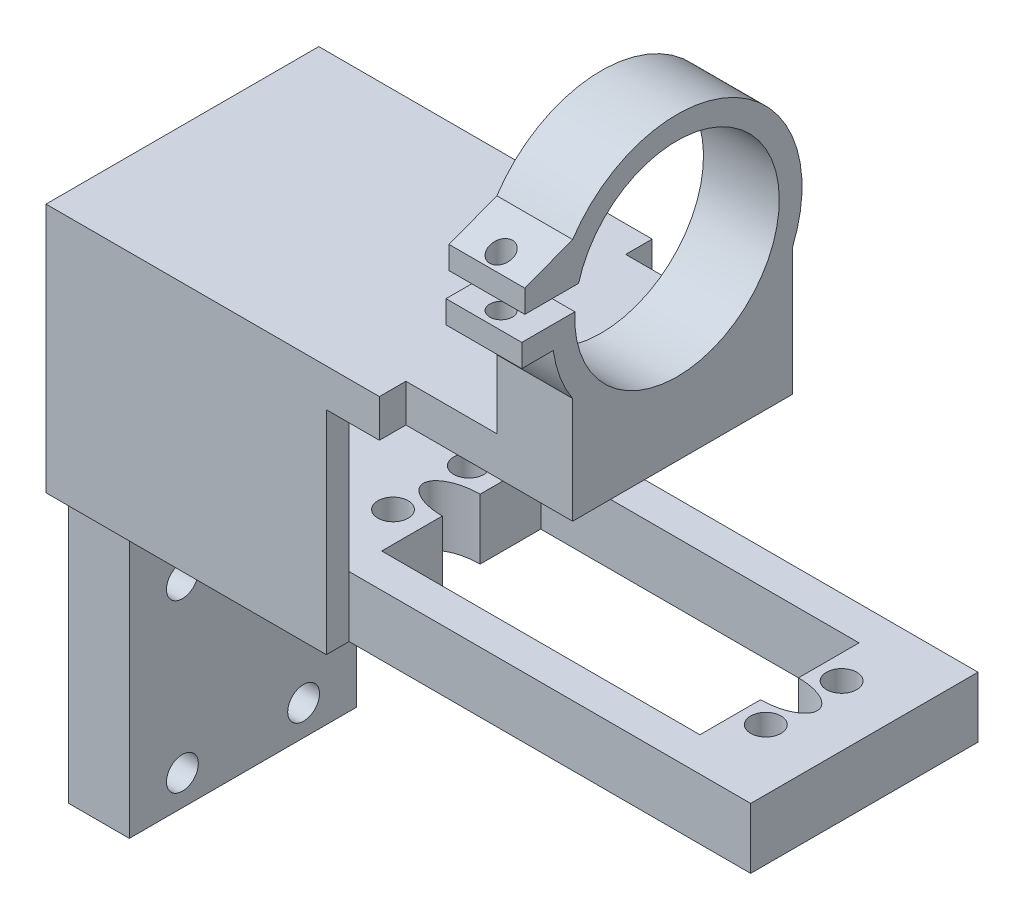
SolidWorks part; units mm, degrees
material "ABS"
ref_plane "前基準面" through (0, 0, 0) normal (0, 0, 1) x (1, 0, 0)
ref_plane "上基準面" through (0, 0, 0) normal (0, 1, 0) x (1, 0, 0)
ref_plane "右基準面" through (0, 0, 0) normal (1, 0, 0) x (0, 0, -1)
sketch "草圖1" plane through (0, 0, 0) normal (0, 1, 0) x (1, 0, 0)
  line L1 (0, 0) -> (82, 0)
  line L2 (0, 0) -> (0, 30)
  line L3 (0, 30) -> (82, 30)
  line L4 (82, 0) -> (82, 30)
  dimension "D1" = 82
  dimension "D2" = 30
extrude "填料-伸長1" add sketch "草圖1" along normal blind 8
sketch "草圖2" plane through (0, 8, 0) normal (0, 1, 0) x (1, 0, 0)
  line L1 (28.8, 25.5) -> (70.8, 25.5)
  line L3 (28.8, 4.5) -> (70.8, 4.5)
  line L6 (82, 30) -> (0, 30) construction
  line L7 (28.8, 25.5) -> (28.8, 17.5)
  line L8 (70.8, 25.5) -> (70.8, 17.5)
  line L9 (70.8, 12.5) -> (70.8, 4.5)
  line L10 (28.8, 12.5) -> (28.8, 4.5)
  line L11 (0, 30) -> (0, 0) construction
  line L12 (82, 0) -> (82, 30) construction
  circle A0 centre (74, 20) radius 2
  circle A1 centre (74, 10) radius 2
  circle A2 centre (24.8, 20) radius 2
  circle A3 centre (24.8, 10) radius 2
  ellipse E0 centre (70.8, 15) end of major axis (75.8, 15) minor radius 2.5 (70.8, 12.5) -> (70.8, 17.5) ccw
  ellipse E1 centre (28.8, 15) end of major axis (33.8, 15) minor radius 2.5 (28.8, 17.5) -> (28.8, 12.5) ccw
  dimension "D4" = 10
  dimension "D1" = 21
  dimension "D2" = 42
  dimension "D3" = 4.5
  dimension "D5" = 10
  dimension "D6" = 10
  dimension "D7" = 10
  dimension "D8" = 5
  dimension "D9" = 5
  dimension "D10" = 10
  dimension "D11" = 8
  dimension "D12" = 10
  dimension "D13" = 8
  dimension "24.8" = 24.8
  dimension "D15" = 8
  dimension "D16" = 28.8
extrude "除料-伸長1" cut sketch "草圖2" against normal blind 8
sketch "草圖4" plane through (0, 8, 0) normal (0, 1, 0) x (1, 0, 0)
  line L0 (0, 30) -> (0, 0)
  line L9 (0, 0) -> (-8, 0)
  line L10 (-8, 0) -> (-8, 30)
  line L11 (-8, 30) -> (0, 30)
  dimension "D1" = 8
extrude "填料-伸長2" add sketch "草圖4" against normal blind 45
sketch "草圖14" plane through (0, 0, 0) normal (0, 0, 1) x (1, 0, 0)
  line L0 (0, 0) -> (0, -2)
  line L1 (0, -37) -> (0, 0) construction
  line L2 (0, -2) -> (2, 0)
  line L3 (0, 0) -> (82, 0) construction
  line L4 (2, 0) -> (0, 0)
  dimension "D1" = 2
  dimension "D2" = 2
extrude "填料-伸長5" add sketch "草圖14" against normal blind 30
sketch "草圖15" plane through (0, 0, 0) normal (1, 0, 0) x (0, 0, -1)
  line L0 (0, -37) -> (30, -37) construction
  line L1 (0, -37) -> (0, -2) construction
  circle A0 centre (7, -33) radius 2.1
  circle A5 centre (7, -11) radius 2.1
  circle A13 centre (23, -11) radius 2.1
  circle A16 centre (23, -33) radius 2.1
  circle A19 centre (15, -11) radius 2.1 [skipped]
  circle A20 centre (15, -33) radius 2.1 [skipped]
  dimension "D1" = 4
  dimension "D2" = 22
  dimension "D3" = 4.2
  dimension "D4" = 4.2
  dimension "D6" = 7
  dimension "D7" = 3
extrude "除料-伸長2" cut sketch "草圖15" against normal blind 10
sketch "草圖17" plane through (0, 8, 0) normal (0, 1, 0) x (1, 0, 0)
  line L1 (-8, 0) -> (29, 0)
  line L2 (-8, 0) -> (-8, -3)
  line L3 (-8, -3) -> (29, -3)
  line L4 (29, 0) -> (29, -3)
  line L5 (-8, 30) -> (29, 30)
  line L6 (-8, 30) -> (-8, 33)
  line L7 (-8, 33) -> (29, 33)
  line L8 (29, 30) -> (29, 33)
  dimension "D1" = 37
  dimension "D2" = 37
  dimension "D3" = 3
  dimension "D4" = 3
extrude "填料-伸長6" add sketch "草圖17" along normal blind 20 separate body
sketch "草圖18" plane through (0, 28, 0) normal (0, 1, 0) x (1, 0, 0)
  line L0 (-8, 33) -> (58, 33)
  line L1 (58, 33) -> (58, -3)
  line L2 (58, -3) -> (-8, -3)
  line L3 (-8, -3) -> (-8, 33)
  dimension "D1" = 66
extrude "填料-伸長7" add sketch "草圖18" along normal blind 5
sketch "草圖19" plane through (0, 8, 0) normal (0, -1, 0) x (-1, 0, 0)
  line L1 (-29, -3) -> (8, -3)
  line L2 (-29, -3) -> (-29, 0)
  line L3 (-29, 0) -> (8, 0)
  line L4 (8, -3) -> (8, 0)
  line L5 (8, 33) -> (-29, 33)
  line L6 (8, 33) -> (8, 30)
  line L7 (8, 30) -> (-29, 30)
  line L8 (-29, 33) -> (-29, 30)
extrude "填料-伸長8" add sketch "草圖19" along normal up to vertex
sketch "草圖20" plane through (0, 33, 0) normal (0, 1, 0) x (1, 0, 0)
  line L0 (58, -3) -> (58, 33) construction
  line L1 (58, 33) -> (36, 33)
  line L2 (58, 33) -> (58, 29.5)
  line L3 (58, 29.5) -> (36, 29.5)
  line L4 (36, 33) -> (36, 29.5)
  line L5 (58, -3) -> (36, -3)
  line L6 (58, -3) -> (58, 0.5)
  line L7 (58, 0.5) -> (36, 0.5)
  line L8 (36, -3) -> (36, 0.5)
  dimension "D1" = 29
  dimension "D2" = 3.5
  dimension "D3" = 22
  dimension "D4" = 22
extrude "除料-伸長3" cut sketch "草圖20" against normal up to vertex (5 mm away)
sketch "草圖21" plane through (58, 0, 0) normal (1, 0, 0) x (0, 0, -1)
  circle A0 centre (14.2747, 51.1133) radius 13.5
  circle A1 centre (14.2747, 51.1133) radius 16.5
  dimension "D1" = 27
  dimension "D2" = 33
extrude "填料-伸長9" add sketch "草圖21" against normal blind 10 separate body
sketch "草圖22" plane through (58, 0, 0) normal (1, 0, 0) x (0, 0, -1)
  line L1 (2.7516, 51.7967) -> (-7.0135, 51.7967)
  line L2 (2.7516, 51.7967) -> (2.7516, 54.7967)
  line L3 (2.7516, 54.7967) -> (-7.0135, 54.7967)
  line L4 (-7.0135, 51.7967) -> (-7.0135, 54.7967)
  point P0 (14.2747, 51.1133)
  dimension "D1" = 3
extrude "除料-伸長4" cut sketch "草圖22" against normal blind 10
sketch "草圖23" plane through (58, 0, 0) normal (1, 0, 0) x (0, 0, -1)
  line L0 (-1.8089, 54.7967) -> (-5.8089, 54.7967)
  line L1 (-5.8089, 54.7967) -> (-5.8089, 57.7967)
  line L2 (-5.8089, 57.7967) -> (0.5, 60.1967)
  line L3 (-2.2111, 51.7967) -> (-6.2111, 51.7967)
  line L4 (-6.2111, 51.7967) -> (-6.2111, 48.7967)
  line L5 (-6.2111, 48.7967) -> (-2.0618, 48.7967)
  line L6 (0.5, 42.03) -> (0.5, 33)
  line L7 (0.5, 33) -> (29.5, 33) construction
  line L8 (0.5, 33) -> (29.5, 33)
  line L9 (29.5, 33) -> (29.5, 44.754)
  line L10 (-1.8089, 54.7967) -> (0.5, 60.1967)
  line L11 (-2.2111, 51.7967) -> (-2.0618, 48.7967)
  line L12 (0.5, 42.03) -> (13.6406, 34.6255)
  line L13 (13.6406, 34.6255) -> (27.6208, 41.4111)
  line L14 (27.6208, 41.4111) -> (29.5, 44.754)
  arc A0 (-2.2111, 51.7967) -> (-1.8089, 54.7967) centre (14.2747, 51.1133) ccw construction
  dimension "D1" = 29
  dimension "D2" = 3
  dimension "D3" = 4
  dimension "D4" = 4
  dimension "D5" = 3
extrude "填料-伸長10" add sketch "草圖23" against normal up to vertex (10 mm away)
sketch "草圖24" plane through (0, 48.7967, 0) normal (0, -1, 0) x (-1, 0, 0)
  line L0 (-48, -6.2111) -> (-58, -6.2111) construction
  line L4 (-48, -6.2111) -> (-48, -2.0618) construction
  circle A0 centre (-53, -3.9311) radius 1.5
  dimension "D1" = 3
  dimension "D2" = 2.28
  dimension "D3" = 5
extrude "除料-伸長5" cut sketch "草圖24" against normal blind 15
